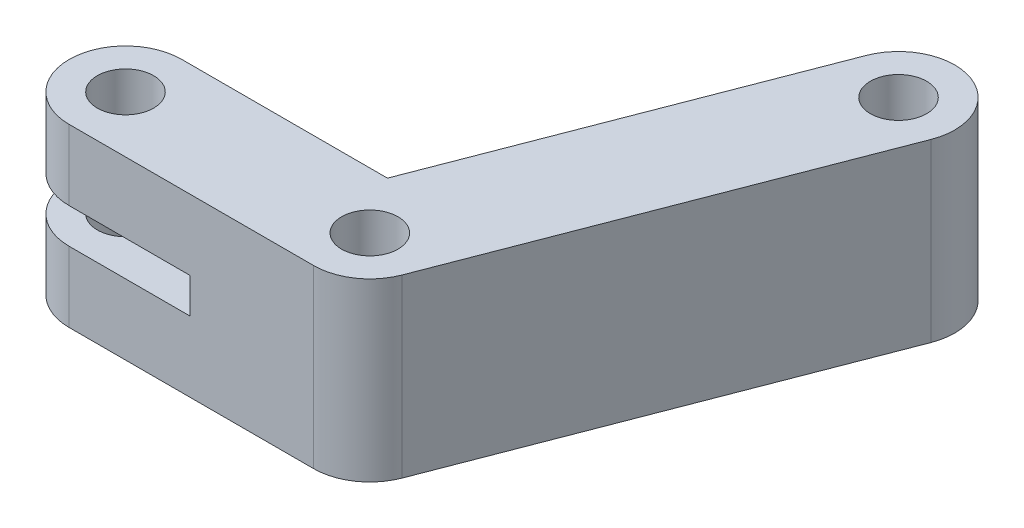
SolidWorks part; units mm, degrees
ref_plane "Front Plane" through (0, 0, 0) normal (0, 0, 1) x (1, 0, 0)
ref_plane "Top Plane" through (0, 0, 0) normal (0, 1, 0) x (1, 0, 0)
ref_plane "Right Plane" through (0, 0, 0) normal (1, 0, 0) x (0, 0, -1)
sketch "Sketch1" plane through (0, 0, 0) normal (0, 1, 0) x (1, 0, 0)
  line L0 (0, 0) -> (34.72, 0) construction
  line L3 (0, 8) -> (29.2283, 8)
  line L6 (0, -8) -> (34.72, -8)
  line L7 (29.2283, 8) -> (48.1445, 57.1152)
  line L8 (63.0755, 51.3648) -> (42.1855, -2.8752)
  line L9 (55.61, 54.24) -> (34.72, 0) construction
  arc A6 (0, 8) -> (0, -8) centre (0, 0) ccw
  arc A8 (48.1445, 57.1152) -> (63.0755, 51.3648) centre (55.61, 54.24) cw
  arc A9 (42.1855, -2.8752) -> (34.72, -8) centre (34.72, 0) cw
  circle A10 centre (0, 0) radius 4
  circle A12 centre (55.61, 54.24) radius 4
  circle A13 centre (34.72, 0) radius 4
  dimension "D2" = 34.72
  dimension "D3" = 8
  dimension "D1" = 8
  dimension "D6" = 8
  dimension "D4" = 54.24
  dimension "D5" = 20.89
extrude "Boss-Extrude1" add sketch "Sketch1" along normal mid plane 25
sketch "Sketch2" plane through (0, 0, 8) normal (0, 0, 1) x (1, 0, 0)
  line L0 (-8, 12.5) -> (-8, -12.5) construction
  line L1 (-8, -2.5) -> (17.15, -2.5)
  line L2 (-8, -2.5) -> (-8, 2.5)
  line L3 (-8, 2.5) -> (17.15, 2.5)
  line L4 (17.15, -2.5) -> (17.15, 2.5)
  line L5 (-8, -2.5) -> (17.15, 2.5) construction
  line L6 (-8, 2.5) -> (17.15, -2.5) construction
  point P0 (4.575, 0)
  dimension "D1" = 5
  dimension "D2" = 25.15
extrude "Cut-Extrude1" cut sketch "Sketch2" against normal up to next
